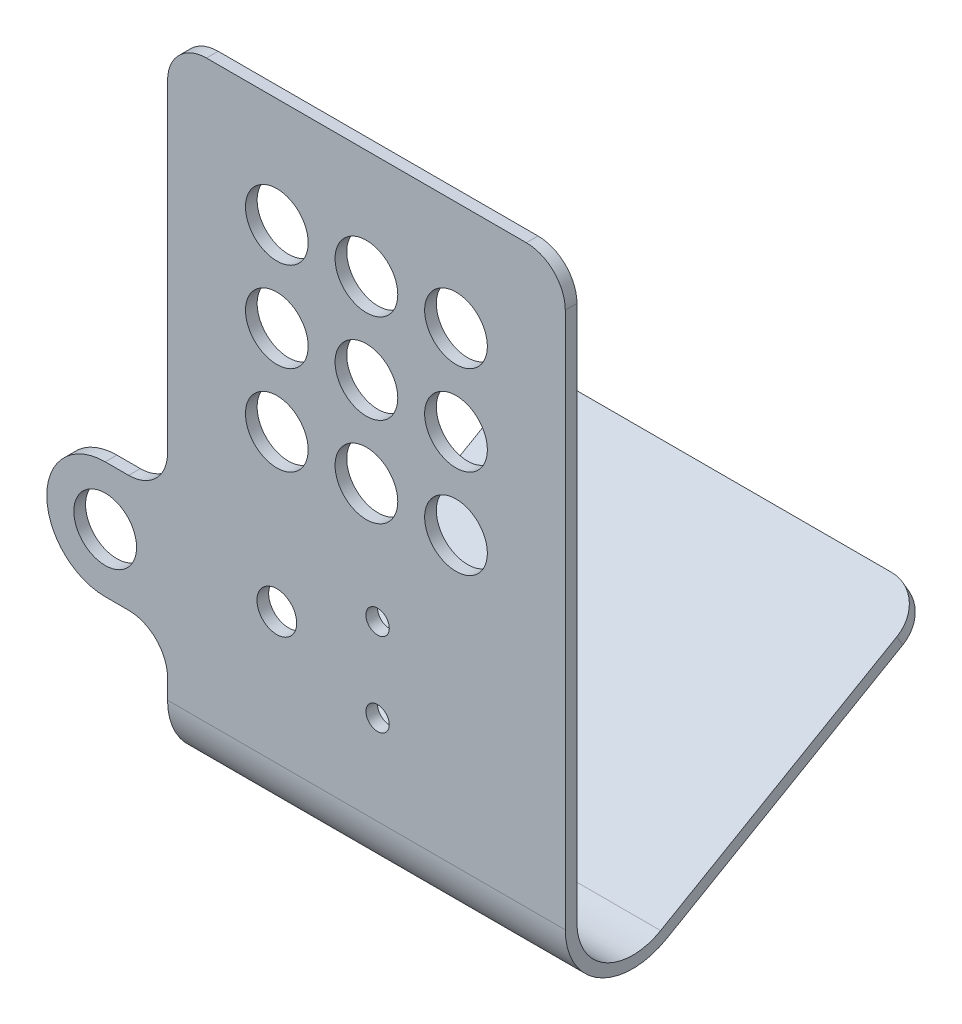
SolidWorks part; units mm, degrees
ref_plane "Front Plane" through (0, 0, 0) normal (0, 0, 1) x (1, 0, 0)
ref_plane "Top Plane" through (0, 0, 0) normal (0, 1, 0) x (1, 0, 0)
ref_plane "Right Plane" through (0, 0, 0) normal (1, 0, 0) x (0, 0, -1)
sketch "Sketch1" plane through (0, 0, 0) normal (0, 0, 1) x (1, 0, 0)
  line L0 (31.05, -23) -> (51.05, -23) construction
  line L1 (51.05, 51.05) -> (-51.05, 51.05)
  line L2 (51.05, 51.05) -> (51.05, -96.7151)
  line L3 (51.05, -96.7151) -> (-51.05, -96.7151)
  line L4 (-51.05, 51.05) -> (-51.05, -96.7151)
  line L5 (0, 31.05) -> (0, 51.05) construction
  line L6 (2.8686, -76.7151) -> (2.8686, -96.7151) construction
  circle A0 centre (-23, 23) radius 8.05
  circle A1 centre (0, 23) radius 8.05
  circle A2 centre (2.8686, -52.2849) radius 3
  circle A3 centre (23, 0) radius 8.05
  circle A4 centre (23, -23) radius 8.05
  circle A5 centre (-23, 0) radius 8.05
  circle A6 centre (0, 0) radius 8.05
  circle A7 centre (-23, -23) radius 8.05
  circle A8 centre (0, -23) radius 8.05
  circle A9 centre (-23, -63) radius 5.1 construction
  circle A10 centre (23, 23) radius 8.05
  circle A11 centre (-23, -63) radius 5.1
  circle A12 centre (2.8686, -52.2849) radius 3 construction
  circle A14 centre (2.8686, -73.7151) radius 3
  circle A15 centre (2.8686, -73.7151) radius 3 construction
  circle A21 centre (-23, -23) radius 8.05 construction
  circle A22 centre (0, -23) radius 8.05 construction
  circle A23 centre (23, -23) radius 8.05 construction
  circle A24 centre (23, 0) radius 8.05 construction
  circle A25 centre (0, 0) radius 8.05 construction
  circle A26 centre (-23, 0) radius 8.05 construction
  circle A27 centre (-23, 23) radius 8.05 construction
  circle A28 centre (0, 23) radius 8.05 construction
  circle A29 centre (23, 23) radius 8.05 construction
  point P65 (0, 51.05)
  dimension "D1" = 20
extrude "Boss-Extrude1" add sketch "Sketch1" against normal blind 3 contours A11 L3 L2 L1 L4 A14 A10 A8 A7 A6 A5 A4 A3 A2 A1 A0
sketch "Sketch2" plane through (-51.05, 0, 0) normal (-1, 0, 0) x (0, 0, 1)
  line L0 (-3, -96.7151) -> (0, -96.7151) construction
  line L2 (-3, 51.05) -> (-3, -96.7151) construction
  line L3 (-24.4808, -109.1171) -> (-93.7628, -69.1171)
  line L4 (-93.7628, -69.1171) -> (-95.2628, -71.7151)
  line L5 (-95.2628, -71.7151) -> (-25.9808, -111.7151)
  line L6 (0, -96.7151) -> (-3, -96.7151)
  line L7 (-24.4808, -109.1171) -> (-25.9808, -111.7151) construction
  line L9 (-24.4808, -109.1171) -> (-3, -96.7151) construction
  line L10 (0, -96.7151) -> (0, -126.7151) construction
  line L11 (0, -126.7151) -> (-25.9808, -111.7151) construction
  line L12 (0, 51.05) -> (0, -96.7151) construction
  arc A0 (-3, -96.7151) -> (-24.4808, -109.1171) centre (-17.3205, -96.7151) cw
  arc A1 (0, -96.7151) -> (-25.9808, -111.7151) centre (-17.3205, -96.7151) cw
  dimension "D1" = 60
  dimension "D2" = 80
  dimension "D3" = 30
extrude "Boss-Extrude2" add sketch "Sketch2" against normal up to surface (102.1 mm away) up to face at (51.05, -22.8326, -1.5)
fillet "Fillet1" radius 10 4 edges at (51.05, -70.4161, -94.5128) (-51.05, -70.4161, -94.5128) (-51.05, 51.05, -1.5) (51.05, 51.05, -1.5)
sketch "Sketch3" plane through (0, 0, -3) normal (0, 0, -1) x (-1, 0, 0)
  line L0 (52.05, -66.7151) -> (51.05, -66.7151) construction
  line L2 (67.05, -51.7151) -> (51.05, -51.7151)
  line L3 (67.05, -81.7151) -> (51.05, -81.7151)
  line L5 (51.05, -51.7151) -> (51.05, -81.7151)
  line L6 (51.05, -81.7151) -> (51.05, -51.7151)
  line L8 (51.05, 41.05) -> (51.05, -96.7151) construction
  line L9 (-51.05, -96.7151) -> (51.05, -96.7151) construction
  circle A0 centre (67.05, -66.7151) radius 15 construction
  arc A1 (67.05, -51.7151) -> (67.05, -81.7151) centre (67.05, -66.7151) cw
  circle A2 centre (67.05, -66.7151) radius 8.05
  circle A4 centre (23, 0) radius 8.05 construction
  dimension "D1" = 30
  dimension "D2" = 1
  dimension "D3" = 30
extrude "Boss-Extrude3" add sketch "Sketch3" against normal up to surface (3 mm away)
fillet "Fillet2" radius 10 2 edges at (-51.05, -51.7151, -1.5) (-51.05, -81.7151, -1.5)
